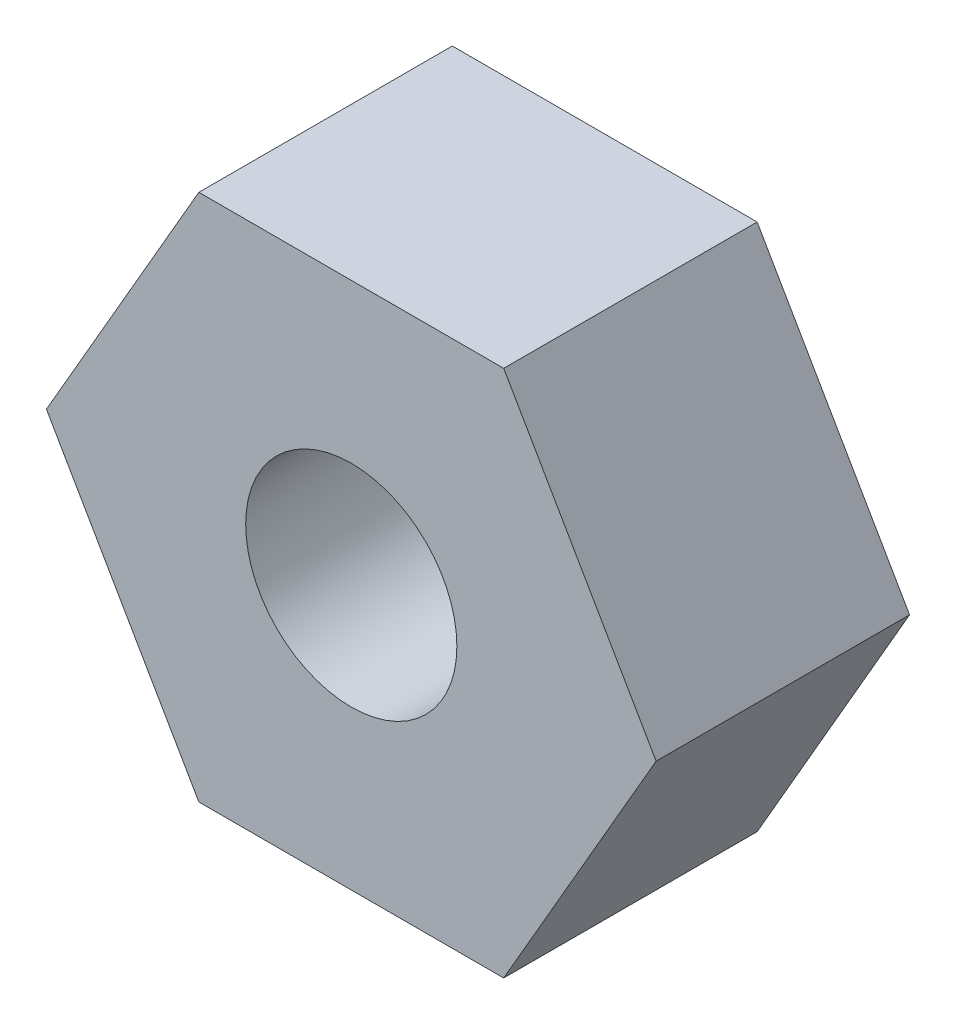
SolidWorks part; units mm, degrees
ref_plane "前视基准面" through (0, 0, 0) normal (0, 0, 1) x (1, 0, 0)
ref_plane "上视基准面" through (0, 0, 0) normal (0, 1, 0) x (1, 0, 0)
ref_plane "右视基准面" through (0, 0, 0) normal (1, 0, 0) x (0, 0, -1)
sketch "草图1" plane through (0, 0, 0) normal (0, 0, 1) x (1, 0, 0)
  line L1 (2.8868, -5) -> (5.7735, 0)
  line L2 (5.7735, 0) -> (2.8868, 5)
  line L3 (2.8868, 5) -> (-2.8868, 5)
  line L4 (-2.8868, 5) -> (-5.7735, 0)
  line L5 (-5.7735, 0) -> (-2.8868, -5)
  line L6 (-2.8868, -5) -> (2.8868, -5)
  circle A0 centre (0, 0) radius 2
  circle A1 centre (0, 0) radius 5 construction
  dimension "D1" = 4
  dimension "D2" = 10
extrude "凸台-拉伸1" add sketch "草图1" along normal blind 4.8
